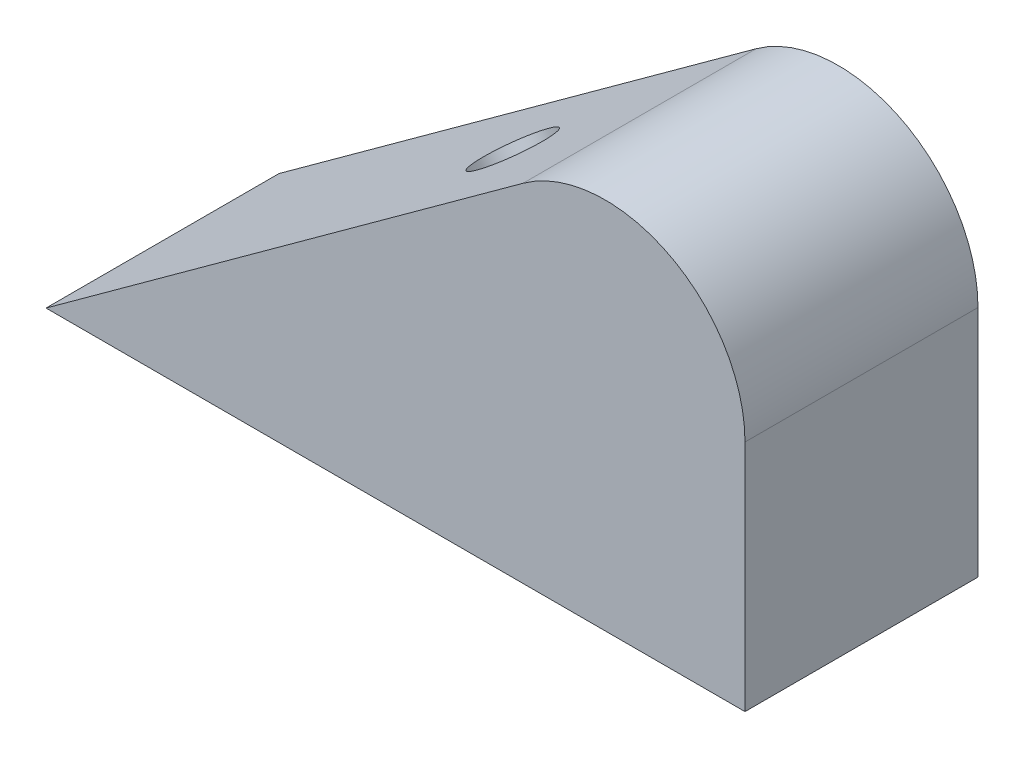
SolidWorks part; units mm, degrees
ref_plane "Front Plane" through (0, 0, 0) normal (0, 0, 1) x (1, 0, 0)
ref_plane "Top Plane" through (0, 0, 0) normal (0, 1, 0) x (1, 0, 0)
ref_plane "Right Plane" through (0, 0, 0) normal (1, 0, 0) x (0, 0, -1)
sketch "Sketch1" plane through (0, 0, 0) normal (0, 0, 1) x (1, 0, 0)
  line L0 (-32.2247, 0) -> (5.8753, 27.6813)
  line L1 (5.8753, 27.6813) -> (5.8753, 0)
  line L2 (5.8753, 0) -> (-32.2247, 0)
  dimension "D1" = 36
  dimension "D2" = 38.1
extrude "Boss-Extrude1" add sketch "Sketch1" along normal blind 12.7
sketch "Sketch2" plane through (0, 0, 0) normal (0, -1, 0) x (1, 0, 0)
  line L0 (-32.2247, 12.7) -> (-32.2247, 0) construction
  line L1 (-32.2247, 0) -> (5.8753, 0) construction
  circle A0 centre (-13.1747, 6.35) radius 2.5797
  dimension "D1" = 5.1594
  dimension "D2" = 19.05
  dimension "D3" = 6.35
extrude "Cut-Extrude1" cut sketch "Sketch2" against normal blind 5.08
sketch "Sketch3" plane through (-11.1334, 15.3238, 0) normal (-0.5878, 0.809, 0) x (0.809, 0.5878, 0)
  line L0 (21.0238, -12.7) -> (21.0238, 0) construction
  line L2 (21.0238, 0) -> (-26.0704, 0) construction
  circle A0 centre (-2.4712, -6.35) radius 1.9844
  dimension "D1" = 3.9688
  dimension "D2" = 23.495
  dimension "D3" = 6.35
extrude "Cut-Extrude2" cut sketch "Sketch3" against normal blind 5.08
fillet "Fillet1" radius 7.62 1 edges at (5.8753, 27.6813, 6.35)
